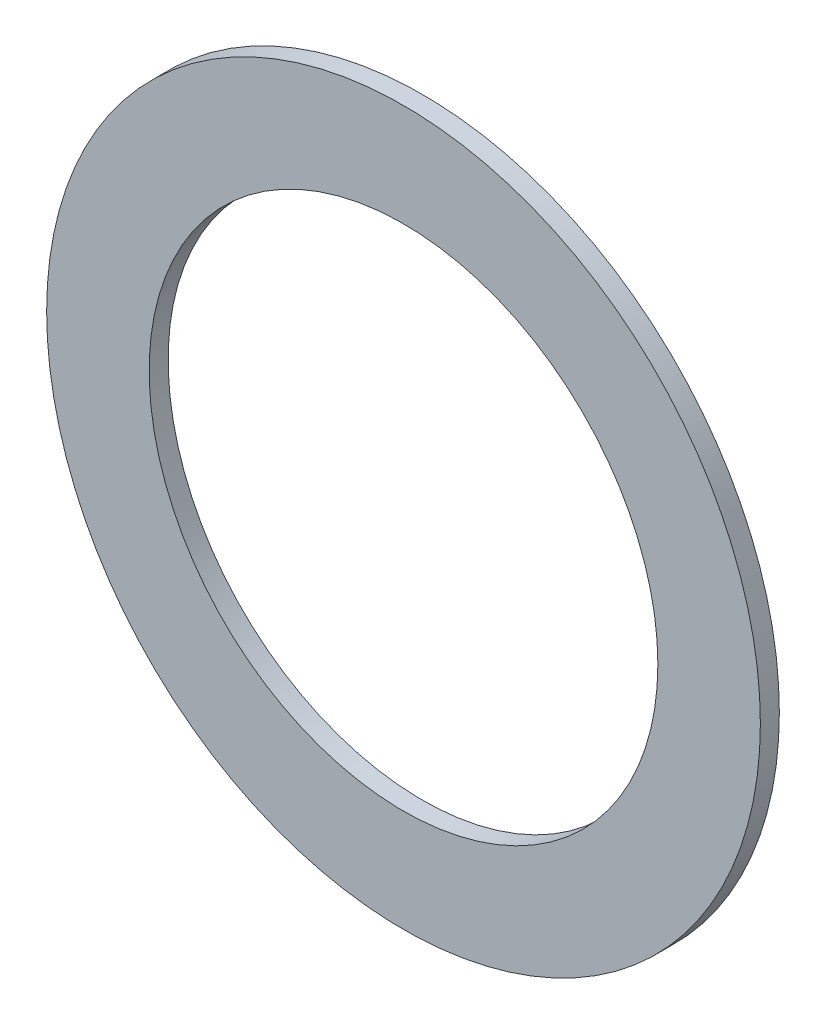
SolidWorks part; units mm, degrees
ref_plane "Ön Düzlem" through (0, 0, 0) normal (0, 0, 1) x (1, 0, 0)
ref_plane "Üst Düzlem" through (0, 0, 0) normal (0, 1, 0) x (1, 0, 0)
ref_plane "Sağ Düzlem" through (0, 0, 0) normal (1, 0, 0) x (0, 0, -1)
sketch "Çizim1" plane through (0, 0, 0) normal (0, 0, 1) x (1, 0, 0)
  circle A0 centre (0, 0) radius 6.7
  circle A1 centre (0, 0) radius 9.4
  dimension "D1" = 18.8
  dimension "D2" = 13.4
extrude "Yükseklik-Ekstrüzyon1" add sketch "Çizim1" along normal blind 0.5
